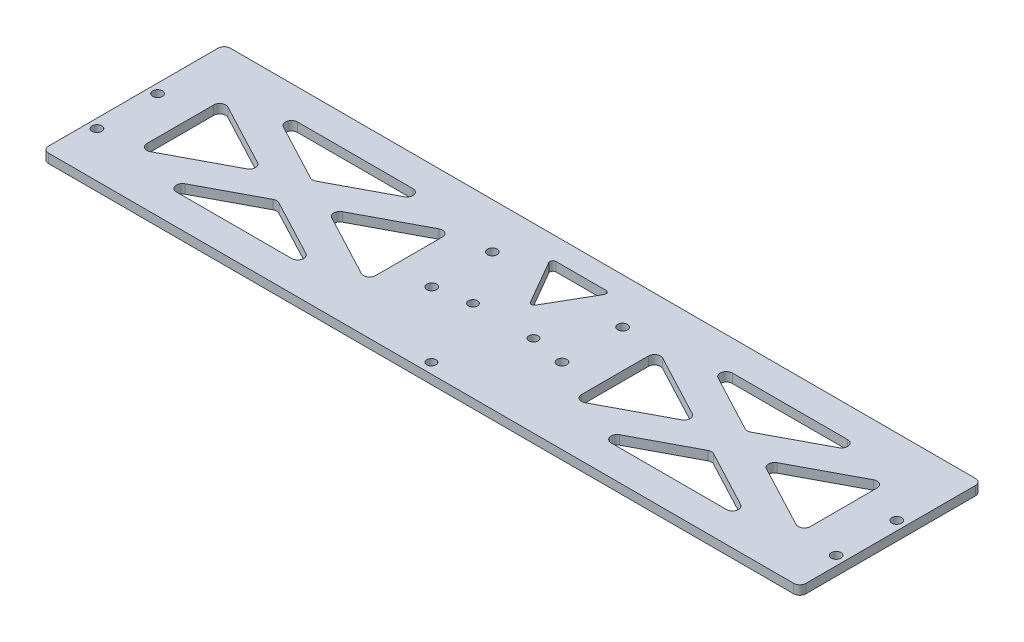
SolidWorks part; units mm, degrees
ref_plane "前视基准面" through (0, 0, 0) normal (0, 0, 1) x (1, 0, 0)
ref_plane "上视基准面" through (0, 0, 0) normal (0, 1, 0) x (1, 0, 0)
ref_plane "右视基准面" through (0, 0, 0) normal (1, 0, 0) x (0, 0, -1)
other "Configuration Table"
sketch "草图1" plane through (0, 0, 0) normal (0, 1, 0) x (1, 0, 0)
  line L1 (-125, 30) -> (125, 30)
  line L2 (-125, 30) -> (-125, -30)
  line L3 (-125, -30) -> (125, -30)
  line L4 (125, 30) -> (125, -30)
  line L5 (-125, 30) -> (125, -30) construction
  line L6 (-125, -30) -> (125, 30) construction
  point P0 (0, 0)
  dimension "D1" = 250
  dimension "D2" = 60
extrude "凸台-拉伸1" add sketch "草图1" along normal blind 3
sketch "草图2" plane through (0, 3, 0) normal (0, 1, 0) x (1, 0, 0)
  circle A0 centre (0, -26.6) radius 1.5
  circle A1 centre (10, -2.9) radius 1.5
  circle A2 centre (-10, -2.9) radius 1.5
  dimension "D1" = 3
extrude "切除-拉伸1" cut sketch "草图2" against normal through all
sketch "草图3" plane through (0, 0, 0) normal (0, -1, 0) x (1, 0, 0)
  circle A0 centre (122, 15) radius 1.6
  circle A1 centre (122, -5) radius 1.6
  circle A2 centre (-122, 15) radius 1.6
  circle A3 centre (-122, -5) radius 1.6
extrude "切除-拉伸2" cut sketch "草图3" against normal through all
sketch "草图4" plane through (0, 3, 0) normal (0, 1, 0) x (1, 0, 0)
  circle A0 centre (-21.5, -5) radius 1.6
  circle A1 centre (-21.5, 15) radius 1.6
  circle A2 centre (21.5, -5) radius 1.6
  circle A3 centre (21.5, 15) radius 1.6
extrude "切除-拉伸3" cut sketch "草图4" against normal through all
fillet "圆角1" radius 2 4 edges at (125, 1.5, -30) (125, 1.5, 30) (-125, 1.5, 30) (-125, 1.5, -30)
sketch "草图5" plane through (0, 3, 0) normal (0, 1, 0) x (1, 0, 0)
  line L0 (123, 30) -> (-123, 30) construction
  line L1 (-109.5, 20) -> (-34, 20)
  line L2 (-109.5, 20) -> (-109.5, -20)
  line L3 (-109.5, -20) -> (-34, -20)
  line L4 (-34, 20) -> (-34, -20)
  line L5 (-123, -30) -> (123, -30) construction
  line L6 (-109.5, 20) -> (-34, -20)
  line L7 (-34, 20) -> (-109.5, -20)
  line L8 (-36.3408, 24.4182) -> (-111.8408, -15.5818)
  line L9 (-111.8408, 15.5818) -> (-36.3408, -24.4182)
  line L10 (-31.6592, 15.5818) -> (-107.1592, -24.4182)
  line L11 (-107.1592, 24.4182) -> (-31.6592, -15.5818)
  circle A0 centre (-122, 5) radius 1.6 construction
  circle A1 centre (-21.5, -5) radius 1.6 construction
  dimension "D1" = 10
  dimension "D2" = 10
  dimension "D3" = 12.5
  dimension "D4" = 12.5
  dimension "D5" = 5
  dimension "D6" = 5
extrude "切除-拉伸4" cut sketch "草图5" against normal through all contours L1 L11 L8 | L10 L11 L4 | L9 L10 L3 | L9 L2 L8
fillet "圆角2" radius 2 12 edges at (-109.5, 1.5, -14.3416) (-82.4302, 1.5, 0) (-109.5, 1.5, 14.3416) (-98.8198, 1.5, 20) (-71.75, 1.5, 5.6584) (-44.6802, 1.5, 20) (-34, 1.5, 14.3416) (-61.0698, 1.5, 0) (-34, 1.5, -14.3416) (-44.6802, 1.5, -20) (-71.75, 1.5, -5.6584) (-98.8198, 1.5, -20)
ref_plane "基准面1" through (0, 0, 0) normal (-1, 0, 0) x (0, 0, 1)
mirror "镜向1" about plane through (0, 0, 0) normal (-1, 0, 0) of "圆角2", "切除-拉伸4"
sketch "草图6" plane through (0, 3, 0) normal (0, 1, 0) x (1, 0, 0)
  line L0 (0, 30) -> (0, -30) construction
  line L1 (123, 30) -> (-123, 30) construction
  line L2 (-123, -30) -> (123, -30) construction
  line L4 (0, 5.453) -> (10, 22.7735)
  line L5 (10, 22.7735) -> (-10, 22.7735)
  line L6 (-10, 22.7735) -> (0, 5.453)
  circle A0 centre (0, 17) radius 5.7735 construction
  point P7 (-11.4048, 18.8068)
  dimension "D1" = 13
  dimension "D2" = 20
extrude "切除-拉伸5" cut sketch "草图6" against normal through all
fillet "圆角3" radius 1 3 edges at (-10, 1.5, -22.7735) (10, 1.5, -22.7735) (0, 1.5, -5.453)
